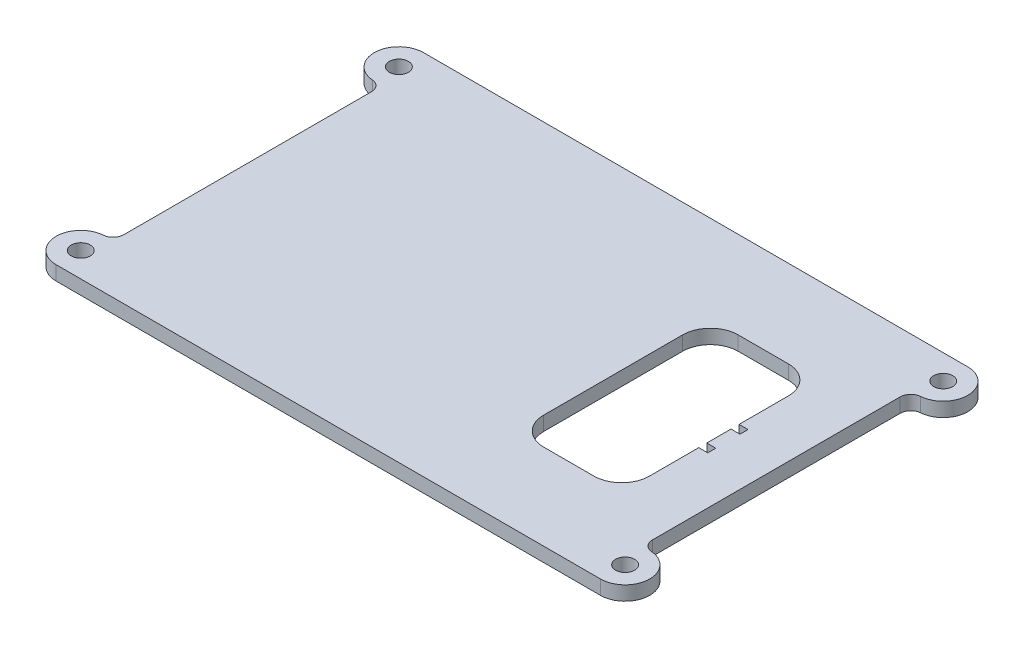
SolidWorks part; units mm, degrees
material "Acrylic (Medium-high impact)"
ref_plane "Front Plane" through (0, 0, 0) normal (0, 0, 1) x (1, 0, 0)
ref_plane "Top Plane" through (0, 0, 0) normal (0, 1, 0) x (1, 0, 0)
ref_plane "Right Plane" through (0, 0, 0) normal (1, 0, 0) x (0, 0, -1)
sketch "Sketch1" plane through (0, 0, 0) normal (0, 1, 0) x (1, 0, 0)
  line L0 (52.8319, -29.2651) -> (52.8319, 26.0254) construction
  line L7 (-66.9181, -42.6198) -> (54.5819, -42.6198) construction
  line L8 (-65.1681, 26.0254) -> (-65.1681, -29.2651) construction
  line L9 (54.5819, 39.3802) -> (-66.9181, 39.3802) construction
  line L10 (52.8319, -29.2651) -> (52.8319, 26.0254)
  line L11 (-66.9181, -42.6198) -> (54.5819, -42.6198)
  line L12 (-65.1681, 26.0254) -> (-65.1681, -29.2651)
  line L13 (54.5819, 39.3802) -> (-66.9181, 39.3802)
  line L14 (40.1639, -6.2648) -> (42.1639, -6.2648) construction
  line L15 (42.1639, -4.4648) -> (42.1639, -6.2648) construction
  line L16 (40.1639, -4.4648) -> (42.1639, -4.4648) construction
  line L17 (40.1639, 0.9352) -> (40.1639, -4.4648) construction
  line L18 (40.1639, 0.9352) -> (42.1639, 0.9352) construction
  line L19 (42.1639, 2.7352) -> (42.1639, 0.9352) construction
  line L20 (40.1639, 2.7352) -> (42.1639, 2.7352) construction
  line L21 (40.1639, 2.7352) -> (40.1639, 13.7352) construction
  line L22 (40.1639, -17.2648) -> (40.1639, -6.2648) construction
  line L23 (22.7639, -23.4648) -> (33.9639, -23.4648) construction
  line L24 (16.5639, 13.7352) -> (16.5639, -17.2648) construction
  line L25 (33.9639, 19.9352) -> (22.7639, 19.9352) construction
  line L26 (40.1639, -6.2648) -> (42.1639, -6.2648)
  line L27 (42.1639, -4.4648) -> (42.1639, -6.2648)
  line L28 (40.1639, -4.4648) -> (42.1639, -4.4648)
  line L29 (40.1639, 0.9352) -> (40.1639, -4.4648)
  line L30 (40.1639, 0.9352) -> (42.1639, 0.9352)
  line L31 (42.1639, 2.7352) -> (42.1639, 0.9352)
  line L32 (40.1639, 2.7352) -> (42.1639, 2.7352)
  line L33 (40.1639, 2.7352) -> (40.1639, 13.7352)
  line L34 (40.1639, -17.2648) -> (40.1639, -6.2648)
  line L35 (22.7639, -23.4648) -> (33.9639, -23.4648)
  line L36 (16.5639, 13.7352) -> (16.5639, -17.2648)
  line L37 (33.9639, 19.9352) -> (22.7639, 19.9352)
  arc A0 (55.0216, 28.3978) -> (54.5819, 39.3802) centre (54.5819, 33.8802) ccw construction
  arc A1 (55.0216, 28.3978) -> (52.8319, 26.0254) centre (55.2119, 26.0254) ccw construction
  arc A2 (52.8319, -29.2651) -> (55.0216, -31.6374) centre (55.2119, -29.2651) ccw construction
  arc A3 (54.5819, -42.6198) -> (55.0216, -31.6374) centre (54.5819, -37.1198) ccw construction
  arc A4 (-67.3578, -31.6374) -> (-66.9181, -42.6198) centre (-66.9181, -37.1198) ccw construction
  arc A5 (-67.3578, -31.6374) -> (-65.1681, -29.2651) centre (-67.5481, -29.2651) ccw construction
  arc A6 (-65.1681, 26.0254) -> (-67.3578, 28.3978) centre (-67.5481, 26.0254) ccw construction
  arc A7 (-66.9181, 39.3802) -> (-67.3578, 28.3978) centre (-66.9181, 33.8802) ccw construction
  arc A8 (55.0216, 28.3978) -> (54.5819, 39.3802) centre (54.5819, 33.8802) ccw
  arc A9 (55.0216, 28.3978) -> (52.8319, 26.0254) centre (55.2119, 26.0254) ccw
  arc A10 (52.8319, -29.2651) -> (55.0216, -31.6374) centre (55.2119, -29.2651) ccw
  arc A11 (54.5819, -42.6198) -> (55.0216, -31.6374) centre (54.5819, -37.1198) ccw
  arc A12 (-67.3578, -31.6374) -> (-66.9181, -42.6198) centre (-66.9181, -37.1198) ccw
  arc A13 (-67.3578, -31.6374) -> (-65.1681, -29.2651) centre (-67.5481, -29.2651) ccw
  arc A14 (-65.1681, 26.0254) -> (-67.3578, 28.3978) centre (-67.5481, 26.0254) ccw
  arc A15 (-66.9181, 39.3802) -> (-67.3578, 28.3978) centre (-66.9181, 33.8802) ccw
  arc A16 (33.9639, -23.4648) -> (40.1639, -17.2648) centre (33.9639, -17.2648) ccw construction
  arc A17 (16.5639, -17.2648) -> (22.7639, -23.4648) centre (22.7639, -17.2648) ccw construction
  arc A18 (22.7639, 19.9352) -> (16.5639, 13.7352) centre (22.7639, 13.7352) ccw construction
  arc A19 (40.1639, 13.7352) -> (33.9639, 19.9352) centre (33.9639, 13.7352) ccw construction
  arc A20 (33.9639, -23.4648) -> (40.1639, -17.2648) centre (33.9639, -17.2648) ccw
  arc A21 (16.5639, -17.2648) -> (22.7639, -23.4648) centre (22.7639, -17.2648) ccw
  arc A22 (22.7639, 19.9352) -> (16.5639, 13.7352) centre (22.7639, 13.7352) ccw
  arc A23 (40.1639, 13.7352) -> (33.9639, 19.9352) centre (33.9639, 13.7352) ccw
  circle A24 centre (-66.9181, 33.8802) radius 2.125
  circle A25 centre (54.5819, 33.8802) radius 2.125
  circle A26 centre (54.5819, -37.1198) radius 2.125
  circle A27 centre (-66.9181, -37.1198) radius 2.125
  point P0 (0, 0)
  dimension "D1" = 4.25
extrude "Boss-Extrude1" add sketch "Sketch1" along normal blind 3.175 contours L13 A15 A14 L12 A13 A12 L11 A11 A10 L10 A9 A8 A27 A26 A25 A24 A23 L33 L32 L31 L30 L29 L28 L27 L26 L34 A20 L35 A21 L36 A22 L37
